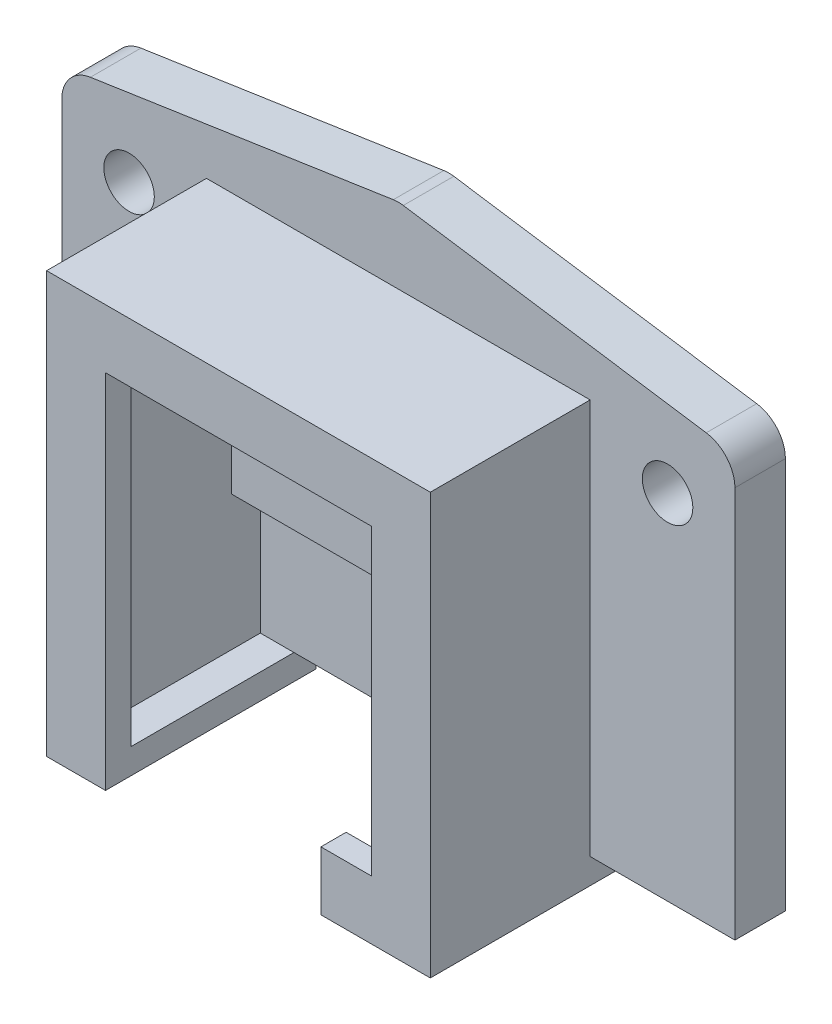
SolidWorks part; units mm, degrees
ref_plane "Alzado" through (0, 0, 0) normal (0, 0, 1) x (1, 0, 0)
ref_plane "Planta" through (0, 0, 0) normal (0, 1, 0) x (1, 0, 0)
ref_plane "Vista lateral" through (0, 0, 0) normal (1, 0, 0) x (0, 0, -1)
sketch "Croquis1" plane through (0, 0, 0) normal (0, 0, 1) x (1, 0, 0)
  line L0 (-55.6033, 22.6375) -> (-73.6033, 19.9375)
  line L2 (-75.3066, 17.9596) -> (-75.3066, -5.318)
  line L3 (-75.3066, -5.318) -> (-35.3066, -5.318)
  line L4 (-35.3066, 17.9596) -> (-35.3066, -5.318)
  line L5 (-55.0099, 22.6375) -> (-37.0099, 19.9375)
  line L6 (-55.3066, 22.682) -> (-35.3066, 22.682) construction
  circle A0 centre (-71.3066, 15.682) radius 1.5
  circle A1 centre (-39.3066, 15.682) radius 1.5
  arc A2 (-37.0099, 19.9375) -> (-35.3066, 17.9596) centre (-37.3066, 17.9596) cw
  arc A3 (-55.6033, 22.6375) -> (-55.0099, 22.6375) centre (-55.3066, 20.6596) cw
  arc A4 (-73.6033, 19.9375) -> (-75.3066, 17.9596) centre (-73.3066, 17.9596) ccw
  point P17 (-75.3066, 19.682)
  dimension "D3" = 2
  dimension "D4" = 32
  dimension "D5" = 3
  dimension "D6" = 3
  dimension "D1" = 7
  dimension "D2" = 3
  dimension "D7" = 4
extrude "Saliente-Extruir1" add sketch "Croquis1" along normal blind 3
sketch "Croquis2" plane through (0, 0, 3) normal (0, 0, 1) x (1, 0, 0)
  line L0 (-75.3066, -5.318) -> (-35.3066, -5.318) construction
  line L1 (-66.7066, -5.318) -> (-65.2066, -5.318)
  line L2 (-66.7066, -5.318) -> (-66.7066, 18.182)
  line L3 (-66.7066, 18.182) -> (-43.9066, 18.182)
  line L4 (-43.9066, -5.318) -> (-43.9066, 18.182)
  line L5 (-45.4066, -5.318) -> (-43.9066, -5.318)
  line L6 (-65.2066, 16.682) -> (-45.4066, 16.682)
  line L7 (-65.2066, 16.682) -> (-65.2066, -5.318)
  line L9 (-45.4066, 16.682) -> (-45.4066, -5.318)
  dimension "D1" = 22.8
  dimension "D3" = 23.5
  dimension "D4" = 1.5
  dimension "D5" = 1.5
  dimension "D6" = 1.5
extrude "Saliente-Extruir2" add sketch "Croquis2" along normal blind 8
sketch "Croquis3" plane through (0, -5.318, 0) normal (0, -1, 0) x (1, 0, 0)
  line L1 (-65.2066, 3) -> (-52.2066, 3)
  line L2 (-65.2066, 3) -> (-65.2066, 1.3)
  line L3 (-65.2066, 1.3) -> (-52.2066, 1.3)
  line L4 (-52.2066, 3) -> (-52.2066, 1.3)
  dimension "D1" = 13
  dimension "D2" = 1.7
extrude "Cortar-Extruir1" cut sketch "Croquis3" against normal blind 8
sketch "Croquis5" plane through (0, -5.318, 0) normal (0, -1, 0) x (1, 0, 0)
  line L0 (-75.3066, 0) -> (-35.3066, 0) construction
  line L1 (-66.7066, 11) -> (-63.2066, 11)
  line L2 (-66.7066, 11) -> (-66.7066, 0)
  line L3 (-66.7066, 0) -> (-63.2066, 0)
  line L4 (-63.2066, 11) -> (-63.2066, 0)
  line L5 (-45.4066, 11) -> (-45.4066, 3) construction
  line L6 (-43.9066, 11) -> (-50.4066, 11)
  line L7 (-43.9066, 11) -> (-43.9066, 0)
  line L8 (-43.9066, 0) -> (-50.4066, 0)
  line L9 (-50.4066, 11) -> (-50.4066, 0)
  line L10 (-65.2066, 11) -> (-65.2066, 1.3) construction
  dimension "D1" = 5
  dimension "D2" = 2
extrude "Saliente-Extruir3" add sketch "Croquis5" along normal blind 1.5
sketch "Croquis6" plane through (0, 0, 11) normal (0, 0, 1) x (1, 0, 0)
  line L0 (-63.2066, -5.318) -> (-63.2066, -6.818)
  line L1 (-63.2066, -6.818) -> (-66.7066, -6.818)
  line L2 (-66.7066, -6.818) -> (-66.7066, 18.182)
  line L3 (-66.7066, 18.182) -> (-43.9066, 18.182)
  line L4 (-43.9066, 18.182) -> (-43.9066, -6.818)
  line L5 (-43.9066, -6.818) -> (-50.4066, -6.818)
  line L6 (-50.4066, -6.818) -> (-50.4066, -3.318)
  line L7 (-50.4066, -3.318) -> (-47.4066, -3.318)
  line L8 (-47.4066, -3.318) -> (-47.4066, 14.682)
  line L9 (-47.4066, 14.682) -> (-63.2066, 14.682)
  line L10 (-63.2066, 14.682) -> (-63.2066, -5.318)
  dimension "D1" = 15.8
extrude "Saliente-Extruir4" add sketch "Croquis6" along normal blind 1.5
